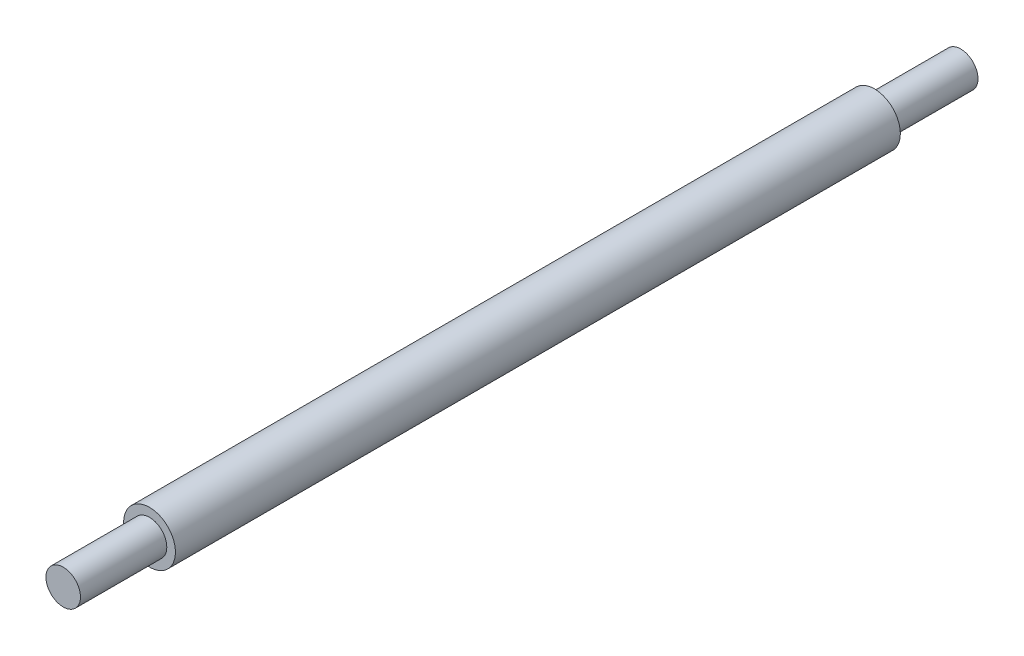
SolidWorks part; units mm, degrees
material "AISI 1020"
ref_plane "Front Plane" through (0, 0, 0) normal (0, 0, 1) x (1, 0, 0)
ref_plane "Top Plane" through (0, 0, 0) normal (0, 1, 0) x (1, 0, 0)
ref_plane "Right Plane" through (0, 0, 0) normal (1, 0, 0) x (0, 0, -1)
sketch "Sketch1" plane through (0, 0, 0) normal (1, 0, 0) x (0, 0, -1)
  line L0 (0, 0) -> (104, 0) construction
  line L1 (0, 0) -> (0, 2)
  line L2 (0, 2) -> (10, 2)
  line L3 (10, 2) -> (10, 3)
  line L4 (10, 3) -> (94, 3)
  line L5 (94, 3) -> (94, 2)
  line L6 (94, 2) -> (104, 2)
  line L7 (104, 2) -> (104, 0)
  line L8 (0, 0) -> (104, 0)
  dimension "D1" = 10
  dimension "D2" = 10
  dimension "D3" = 104
  dimension "D4" = 2
  dimension "D5" = 3
revolve "Revolve1" add sketch "Sketch1" angle 360 about L0
